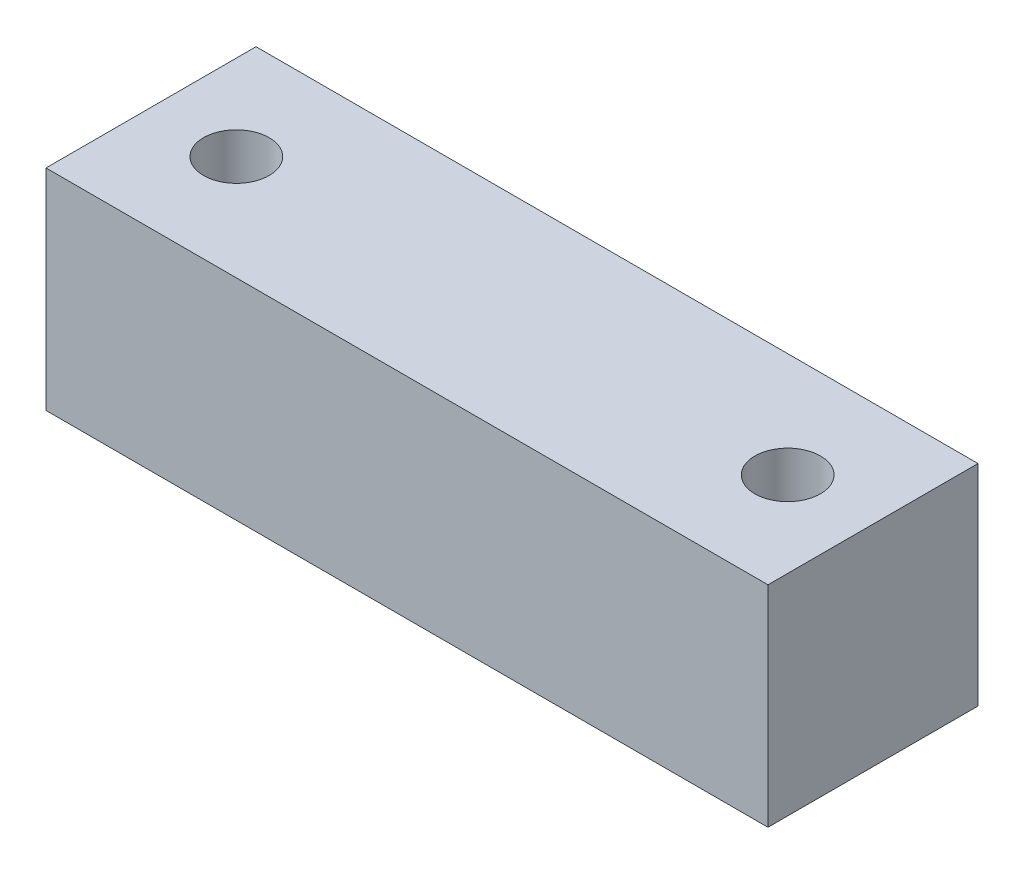
SolidWorks part; units mm, degrees
ref_plane "Front Plane" through (0, 0, 0) normal (0, 0, 1) x (1, 0, 0)
ref_plane "Top Plane" through (0, 0, 0) normal (0, 1, 0) x (1, 0, 0)
ref_plane "Right Plane" through (0, 0, 0) normal (1, 0, 0) x (0, 0, -1)
sketch "Sketch1" plane through (0, 0, 0) normal (0, 1, 0) x (1, 0, 0)
  line L1 (0, 0) -> (55, 0)
  line L2 (0, 0) -> (0, 8)
  line L3 (0, 8) -> (55, 8)
  line L4 (55, 0) -> (55, 8)
  dimension "D1" = 55
  dimension "D2" = 8
extrude "Boss-Extrude1" add sketch "Sketch1" along normal blind 16
sketch "Sketch2" plane through (0, 16, 0) normal (0, 1, 0) x (1, 0, 0)
  line L0 (0, 8) -> (0, 0) construction
  circle A0 centre (6.5, 4) radius 2.5
  circle A1 centre (48.5, 4) radius 2.5
  point P6 (0, 4)
  dimension "D2" = 5
  dimension "D3" = 5
  dimension "D1" = 42
  dimension "D4" = 6.5
extrude "Cut-Extrude1" cut sketch "Sketch2" against normal blind 16
sketch "Sketch3" plane through (0, 0, 0) normal (0, 0, 1) x (1, 0, 0)
  line L1 (0, 16) -> (55, 16)
  line L2 (0, 16) -> (0, 0)
  line L3 (0, 0) -> (55, 0)
  line L4 (55, 16) -> (55, 0)
extrude "Boss-Extrude2" add sketch "Sketch3" along normal blind 4
sketch "Sketch4" plane through (0, 0, -8) normal (0, 0, -1) x (-1, 0, 0)
  line L1 (-55, 0) -> (0, 0)
  line L2 (-55, 0) -> (-55, 16)
  line L3 (-55, 16) -> (0, 16)
  line L4 (0, 0) -> (0, 16)
extrude "Boss-Extrude3" add sketch "Sketch4" along normal blind 4
equation "\"6.5.00mm\"=4"
